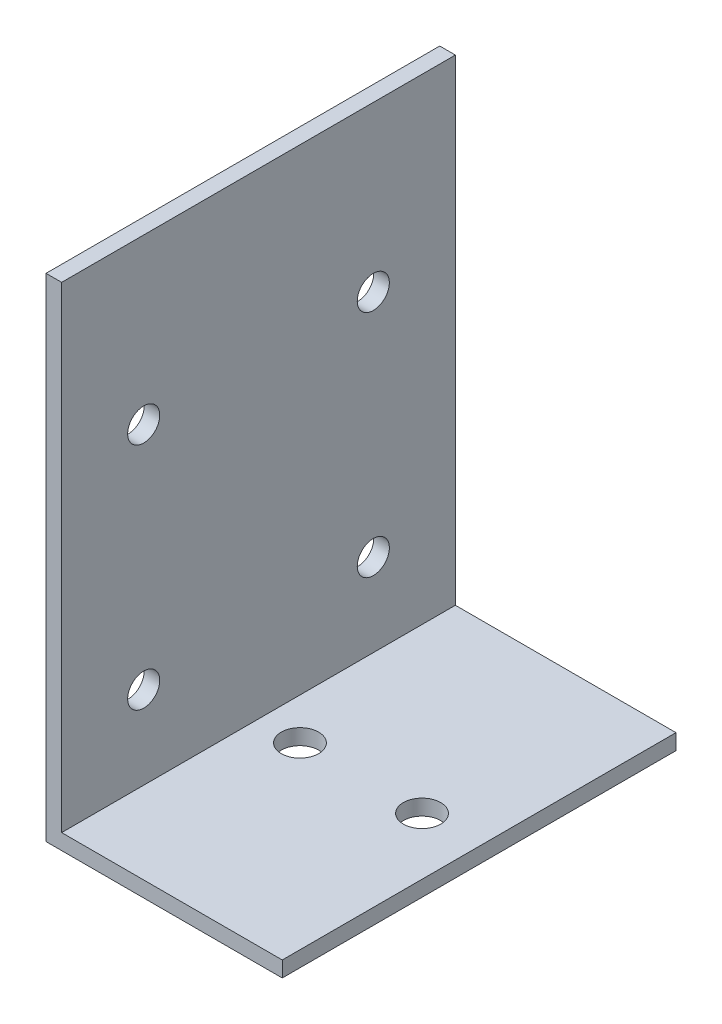
SolidWorks part; units mm, degrees
ref_plane "Front Plane" through (0, 0, 0) normal (0, 0, 1) x (1, 0, 0)
ref_plane "Top Plane" through (0, 0, 0) normal (0, 1, 0) x (1, 0, 0)
ref_plane "Right Plane" through (0, 0, 0) normal (1, 0, 0) x (0, 0, -1)
sketch "Sketch1" plane through (0, 0, 0) normal (0, 0, 1) x (1, 0, 0)
  line L0 (0, 50) -> (0, 0)
  line L1 (0, 0) -> (24, 0)
  line L2 (1.5875, 50) -> (1.5875, 1.5875)
  line L3 (1.5875, 1.5875) -> (24, 1.5875)
  line L4 (0, 50) -> (1.5875, 50)
  line L5 (24, 1.5875) -> (24, 0)
  dimension "D1" = 50
  dimension "D2" = 24
  dimension "D3" = 1.5875
extrude "Boss-Extrude1" add sketch "Sketch1" along normal blind 20
hole_wizard "#4 Clearance Hole1" positions "Sketch3" profile "Sketch2" hole size "#4" standard "ANSI Inch" end condition through all
sketch "Sketch3" plane through (0, 0, 0) normal (-1, 0, 0) x (0, 0, 1)
  line L0 (0, 50) -> (0, 0) construction
  line L1 (20, 0) -> (0, 0) construction
  point P0 (11.6625, 33.325)
  point P2 (11.6625, 10)
  dimension "D1" = 11.6625
  dimension "D2" = 23.325
  dimension "D3" = 10
sketch "Sketch2" plane through (0, 33.325, 11.6625) normal (0, 1, 0) x (0, 0, 1)
  line L0 (0, 0) -> (0, 24)
  line L1 (0, 24) -> (1.6319, 24)
  line L2 (1.6319, 24) -> (1.6319, 0)
  line L5 (1.6319, 0) -> (0, 0)
  line L11 (0, -6.35) -> (0, 107.95) construction
  dimension "Thru Hole Dia." = 3.2639
  dimension "Thru Hole Depth" = 24
mirror "Mirror1" about plane through (0, 0, 0) normal (0, 0, -1) of "Boss-Extrude1", "#4 Clearance Hole1"
hole_wizard "#6 Clearance Hole1" positions "Sketch5" profile "Sketch4" hole size "#6" standard "ANSI Inch" end condition through all
sketch "Sketch5" plane through (0, 0, 0) normal (0, -1, 0) x (-1, 0, 0)
  line L0 (-12, 20) -> (-12, -20) construction
  line L1 (0, 20) -> (-24, 20) construction
  line L2 (0, -20) -> (-24, -20) construction
  line L4 (0, 0) -> (-24, 0) construction
  line L5 (-24, -20) -> (-24, 20) construction
  point P0 (-18.2, 0)
  point P18 (-5.8, 0)
  dimension "D1" = 6.2
sketch "Sketch4" plane through (18.2, 0, 0) normal (1, 0, 0) x (0, 0, -1)
  line L0 (0, 0) -> (0, 50)
  line L1 (0, 50) -> (1.8986, 50)
  line L2 (1.8986, 50) -> (1.8986, 0)
  line L5 (1.8986, 0) -> (0, 0)
  line L11 (0, -6.35) -> (0, 107.95) construction
  dimension "Thru Hole Dia." = 3.7973
  dimension "Thru Hole Depth" = 50
